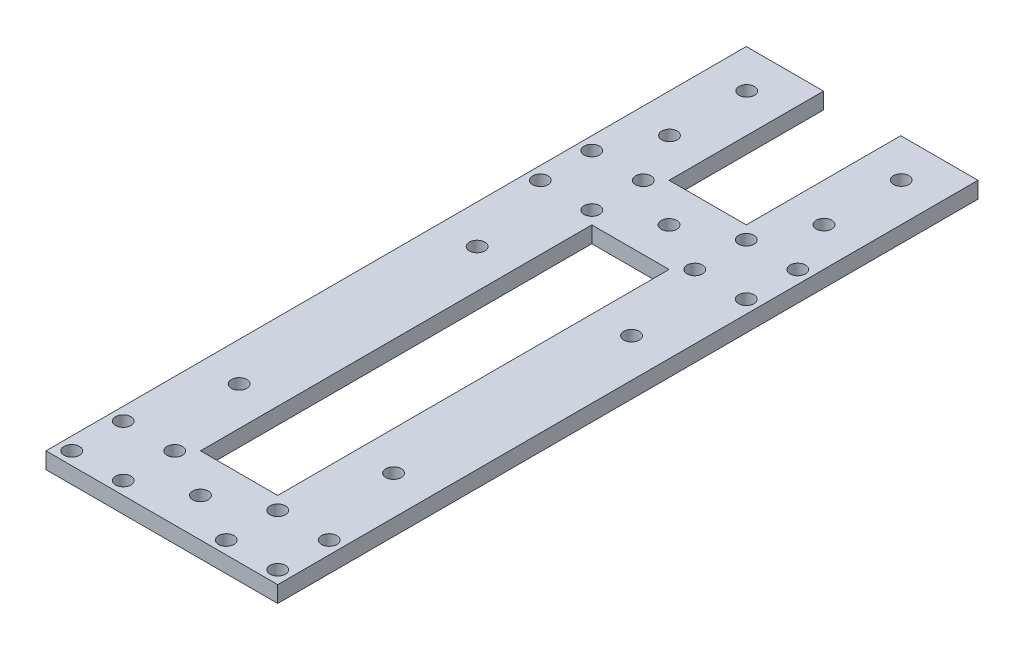
SolidWorks part; units mm, degrees
ref_plane "Front Plane" through (0, 0, 0) normal (0, 0, 1) x (1, 0, 0)
ref_plane "Top Plane" through (0, 0, 0) normal (0, 1, 0) x (1, 0, 0)
ref_plane "Right Plane" through (0, 0, 0) normal (1, 0, 0) x (0, 0, -1)
sketch "Sketch1" plane through (0, 0, 0) normal (0, 1, 0) x (1, 0, 0)
  line L0 (95.5951, -9.673) -> (140.5951, -9.673)
  line L1 (95.5951, 43.327) -> (140.5951, 43.327)
  line L2 (95.5951, 43.327) -> (95.5951, -62.673)
  line L3 (95.5951, -62.673) -> (140.5951, -62.673)
  line L4 (140.5951, 43.327) -> (140.5951, -62.673)
  line L5 (118.0951, -62.673) -> (118.0951, 43.327)
  line L7 (110.5951, -47.673) -> (125.5951, -47.673)
  line L8 (110.5951, -47.673) -> (110.5951, 28.327)
  line L9 (110.5951, 28.327) -> (125.5951, 28.327)
  line L10 (125.5951, -47.673) -> (125.5951, 28.327)
  line L11 (110.5951, -47.673) -> (125.5951, 28.327) construction
  line L12 (110.5951, 28.327) -> (125.5951, -47.673) construction
  point P8 (118.0951, -9.673)
  dimension "D1" = 106
  dimension "D2" = 76
  dimension "D3" = 15
  dimension "D4" = 45
extrude "Boss-Extrude1" add sketch "Sketch1" along normal blind 3.175 contours L7 L8 L0 L2 L3 L5 | L8 L9 L5 L1 L2 L0 | L10 L0 L4 L1 L5 L9 | L10 L7 L5 L3 L4 L0
sketch "Sketch2" plane through (0, 0, 0) normal (0, -1, 0) x (1, 0, 0)
  line L0 (140.5951, -43.327) -> (125.5951, -28.327)
  line L1 (133.0951, -35.827) -> (138.0943, -40.8262)
  line L2 (140.5951, 9.673) -> (95.5951, 9.673)
  line L5 (118.0951, -43.327) -> (118.0951, 62.673)
  line L6 (95.5951, -43.327) -> (140.5951, -43.327) construction
  line L7 (95.5951, 62.673) -> (140.5951, 62.673) construction
  line L8 (140.5951, -43.327) -> (140.5951, 62.673) construction
  line L9 (95.5951, -43.327) -> (95.5951, 62.673) construction
  arc A0 (138.0943, -40.8262) -> (128.0958, -40.8262) centre (133.0951, -35.827) ccw
  circle A1 centre (128.0958, -40.8262) radius 1.5
  circle A2 centre (138.0943, -40.8262) radius 1.5
  arc A3 (138.0943, -30.8278) -> (128.0958, -30.8278) centre (133.0951, -35.827) ccw
  circle A4 centre (138.0943, -30.8278) radius 1.5
  circle A5 centre (128.0958, -30.8278) radius 1.5
  circle A6 centre (138.0943, 60.1722) radius 1.5
  circle A7 centre (138.0943, 50.1738) radius 1.5
  circle A8 centre (128.0958, 50.1738) radius 1.5
  circle A9 centre (128.0958, 60.1722) radius 1.5
  circle A10 centre (98.0958, -40.8262) radius 1.5
  circle A11 centre (98.0958, -30.8278) radius 1.5
  circle A12 centre (108.0943, -30.8278) radius 1.5
  circle A13 centre (108.0943, -40.8262) radius 1.5
  circle A14 centre (98.0958, 50.1738) radius 1.5
  circle A15 centre (98.0958, 60.1722) radius 1.5
  circle A16 centre (108.0943, 60.1722) radius 1.5
  circle A17 centre (108.0943, 50.1738) radius 1.5
extrude "Cut-Extrude1" cut sketch "Sketch2" against normal through all contours A7 | A6 | A9 | A8 | A16 | A17 | A15 | A14 | A11 | A12 | A13 | A10 | A1 | A5 | A4 | A2
sketch "Sketch4" plane through (0, 0, 0) normal (0, -1, 0) x (1, 0, 0)
  line L0 (125.5951, 47.673) -> (140.5951, 47.673)
  line L1 (140.5951, -43.327) -> (140.5951, 62.673) construction
  line L2 (140.5951, -28.772) -> (125.5951, -28.327)
  line L3 (133.0951, 47.673) -> (133.0951, 32.673)
  line L4 (133.0951, -28.5495) -> (133.0951, -13.5495)
  line L5 (118.0951, 47.673) -> (118.0951, -28.327)
  line L6 (110.5951, 47.673) -> (125.5951, 47.673) construction
  line L7 (110.5951, -28.327) -> (125.5951, -28.327) construction
  circle A0 centre (133.0951, 32.673) radius 1.5
  circle A1 centre (133.0951, -13.5495) radius 1.5
  circle A2 centre (103.0951, -13.5495) radius 1.5
  circle A3 centre (103.0951, 32.673) radius 1.5
  dimension "D1" = 15
extrude "Cut-Extrude2" cut sketch "Sketch4" against normal through all contours A1 | A0 | A2 | A3
sketch "Sketch5" plane through (0, 0, 0) normal (0, -1, 0) x (1, 0, 0)
  line L0 (140.5951, -43.327) -> (95.5951, -43.327)
  line L1 (140.5951, -43.327) -> (140.5951, -73.327)
  line L2 (95.5951, -43.327) -> (95.5951, -73.327)
  line L3 (140.5951, -73.327) -> (95.5951, -73.327)
  line L4 (125.5951, -28.327) -> (125.5951, -43.327)
  line L5 (110.5951, -28.327) -> (110.5951, -43.327)
  line L6 (125.5951, -43.327) -> (110.5951, -43.327)
  line L7 (125.5951, -43.327) -> (125.5951, -73.5046)
  line L8 (110.5951, -43.327) -> (110.5951, -73.5046)
  line L9 (125.5951, -73.5046) -> (110.5951, -73.5046)
  line L10 (140.5951, -43.327) -> (125.5951, -73.5046)
  line L11 (140.5951, -73.327) -> (125.5951, -43.327)
  line L12 (133.0951, -58.4158) -> (133.0951, -50.9158)
  line L13 (133.0951, -58.4158) -> (133.0951, -65.9158)
  line L14 (118.0951, -43.327) -> (118.0951, -73.327)
  circle A0 centre (133.0951, -65.9158) radius 1.5
  circle A1 centre (133.0951, -50.9158) radius 1.5
  circle A2 centre (103.0951, -65.9158) radius 1.5
  circle A3 centre (103.0951, -50.9158) radius 1.5
  dimension "D1" = 30
extrude "Boss-Extrude2" add sketch "Sketch5" against normal blind 3.175
sketch "Sketch6" plane through (0, 3.175, 0) normal (0, 1, 0) x (1, 0, 0)
  line L0 (125.5951, -9.673) -> (110.5951, -9.673)
  line L1 (125.5951, -47.673) -> (125.5951, 28.327) construction
  line L2 (110.5951, -47.673) -> (110.5951, 28.327) construction
  line L3 (118.0951, -47.673) -> (118.0951, -62.673)
  line L4 (110.5951, -47.673) -> (125.5951, -47.673) construction
  line L5 (95.5951, -62.673) -> (140.5951, -62.673) construction
  circle A0 centre (118.0951, -55.173) radius 1.5
  circle A1 centre (118.0951, 35.827) radius 1.5
extrude "Cut-Extrude3" cut sketch "Sketch6" against normal through all contours A1 | A0
